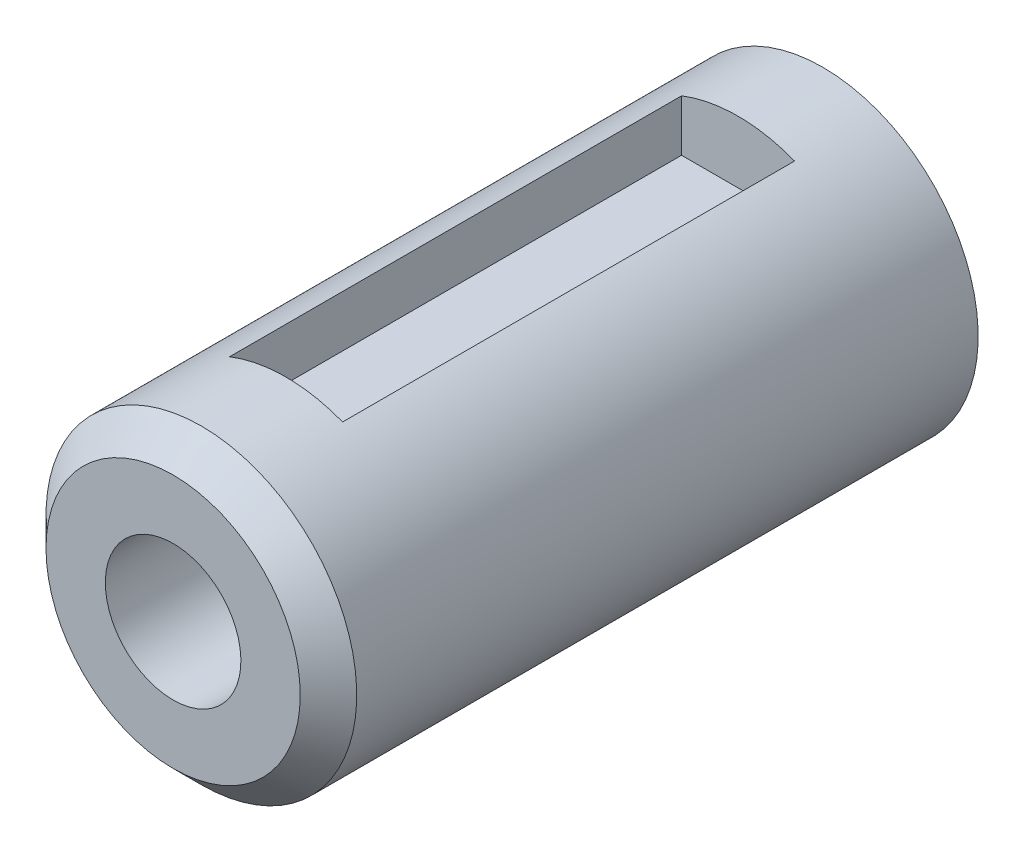
SolidWorks part; units mm, degrees
ref_plane "Спереди" through (0, 0, 0) normal (0, 0, 1) x (1, 0, 0)
ref_plane "Сверху" through (0, 0, 0) normal (0, 1, 0) x (1, 0, 0)
ref_plane "Справа" through (0, 0, 0) normal (1, 0, 0) x (0, 0, -1)
sketch "Эскиз1" plane through (0, 0, 0) normal (1, 0, 0) x (0, 0, -1)
  line L0 (0, 0) -> (-23, 0)
  line L1 (-23, 0) -> (-23, -4.5)
  line L2 (-22, -5.5) -> (0, -5.5)
  line L3 (0, -5.5) -> (0, 0)
  line L4 (-25.6683, 0) -> (3.0719, 0)
  line L5 (-28.6504, 0) -> (8.8258, 0)
  line L9 (-23, -4.5) -> (-22, -5.5)
revolve "Повернуть1" add sketch "Эскиз1" angle 360 about L5
sketch "Эскиз2" plane through (0, 0, 23) normal (0, 0, 1) x (1, 0, 0)
  point P0 (0, 0)
hole_wizard "Отверстие с зазором M41" positions "Трехмерный эскиз1" profile "Эскиз3" hole size "M4" standard "ГОСТ"
sketch3d "Трехмерный эскиз1"
  point P0 (0, 0, 23)
sketch "Эскиз3" plane through (0, 0, 23) normal (1, 0, 0) x (0, -1, 0)
  line L0 (0, 0) -> (0, 17.4421)
  line L1 (0, 17.4421) -> (2.4, 16)
  line L2 (2.4, 16) -> (2.4, 0)
  line L5 (2.4, 0) -> (0, 0)
  line L10 (0, 17.4421) -> (-2.4, 16) construction
  line L11 (0, -6.35) -> (0, 107.95) construction
  dimension "Диаметр отверстия" = 4.8
  dimension "Глубина отверстия" = 16
  dimension "Угол заточки сверла" = 118
sketch3d "Трехмерный эскиз2" plane through (0, 0, 0) normal (0, 0, 1) x (1, 0, 0)
ref_plane "Плоскость1" through (0, 5.5, 0) normal (0, 1, 0) x (1, 0, 0)
sketch "Эскиз4" plane through (0, 5.5, 0) normal (0, 1, 0) x (1, 0, 0)
  line L0 (0, 0) -> (0, -43.668)
  line L1 (5.5, -22) -> (-5.5, -22) construction
  line L2 (0, -22) -> (0, 0)
  line L3 (0, -22) -> (0, -19)
  line L4 (0, -19) -> (2, -19)
  line L5 (0, -19) -> (-2, -19)
  line L6 (-2, -19) -> (-2, -3)
  line L7 (-2, -3) -> (2, -3)
  line L8 (2, -3) -> (2, -19)
  point P5 (0, -22)
extrude "Вырез-Вытянуть1" cut sketch "Эскиз4" against normal blind 2.2 contours L5 L6 L7 L8 L4
